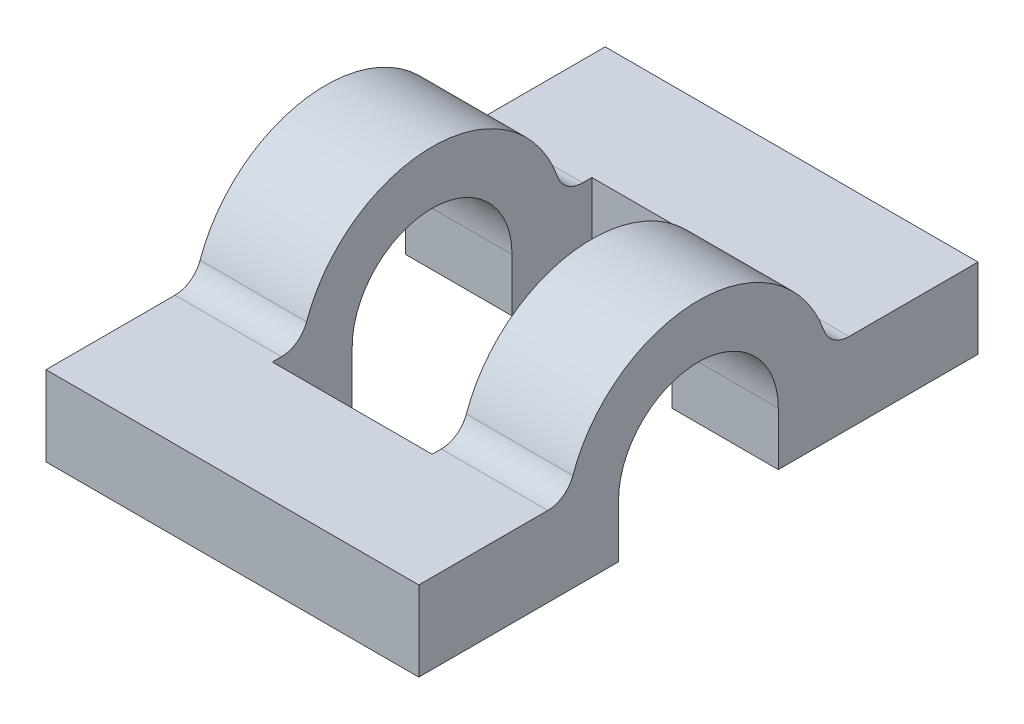
SolidWorks part; units mm, degrees
ref_plane "前视基准面" through (0, 0, 0) normal (0, 0, 1) x (1, 0, 0)
ref_plane "上视基准面" through (0, 0, 0) normal (0, 1, 0) x (1, 0, 0)
ref_plane "右视基准面" through (0, 0, 0) normal (1, 0, 0) x (0, 0, -1)
sketch "草图2" plane through (0, 0, 0) normal (1, 0, 0) x (0, 0, -1)
  line L0 (10.5, 0) -> (3, 0)
  line L1 (10.5, 0) -> (10.5, 3)
  line L2 (10.5, 3) -> (4.899, 3)
  line L3 (-4.899, 3) -> (-10.5, 3)
  line L4 (-10.5, 3) -> (-10.5, 0)
  line L5 (-10.5, 0) -> (-3, 0)
  line L6 (3, 0) -> (3, 2)
  line L7 (-3, 0) -> (-3, 2)
  arc A0 (-3, 2) -> (3, 2) centre (0, 2) cw
  arc A1 (-4.899, 3) -> (4.899, 3) centre (0, 2) cw
  dimension "D2" = 3
  dimension "D3" = 2
  dimension "D4" = 5
  dimension "D1" = 3
  dimension "D5" = 7.5
  dimension "D6" = 7.5
  dimension "D7" = 3
extrude "凸台-拉伸1" add sketch "草图2" along normal blind 14
sketch "草图3" plane through (0, 0, 0) normal (0, -1, 0) x (1, 0, 0)
  line L0 (0, 10.5) -> (0, 3) construction
  line L1 (4, 6) -> (10, 6)
  line L2 (4, 6) -> (4, -6)
  line L3 (4, -6) -> (10, -6)
  line L4 (10, 6) -> (10, -6)
  dimension "D1" = 6
  dimension "D2" = 4
  dimension "D3" = 6
  dimension "D4" = 12
extrude "切除-拉伸1" cut sketch "草图3" against normal through all
fillet "圆角2" radius 1 4 edges at (2, 3, 4.899) (12, 3, 4.899) (2, 3, -4.899) (12, 3, -4.899)
